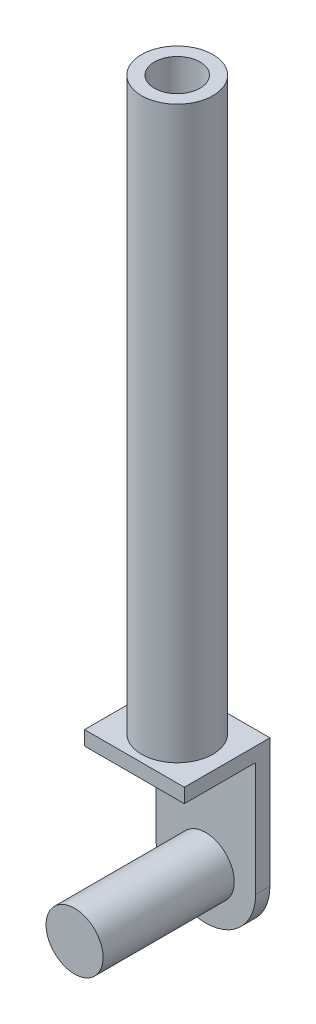
SolidWorks part; units mm, degrees
ref_plane "前视基准面" through (0, 0, 0) normal (0, 0, 1) x (1, 0, 0)
ref_plane "上视基准面" through (0, 0, 0) normal (0, 1, 0) x (1, 0, 0)
ref_plane "右视基准面" through (0, 0, 0) normal (1, 0, 0) x (0, 0, -1)
sketch "草图1" plane through (0, 0, 0) normal (0, 0, 1) x (1, 0, 0)
  line L0 (-17.5, 0) -> (-17.5, 40)
  line L1 (-17.5, 40) -> (17.5, 40)
  line L2 (17.5, 40) -> (17.5, 0)
  circle A0 centre (0, 0) radius 10 construction
  arc A1 (-17.5, 0) -> (17.5, 0) centre (0, 0) ccw
  dimension "D1" = 20
  dimension "D2" = 35
  dimension "D3" = 40
extrude "凸台-拉伸1" add sketch "草图1" along normal blind 5
sketch "草图2" plane through (0, 0, 5) normal (0, 0, 1) x (1, 0, 0)
  circle A0 centre (0, 0) radius 10
  dimension "D1" = 20
extrude "凸台-拉伸2" add sketch "草图2" along normal blind 46
sketch "草图4" plane through (0, 40, 0) normal (0, 1, 0) x (1, 0, 0)
  line L0 (17.5, -5) -> (17.5, 0) construction
  line L1 (-17.5, 0) -> (17.5, 0)
  line L2 (-17.5, 0) -> (-17.5, -30)
  line L3 (-17.5, -30) -> (17.5, -30)
  line L4 (17.5, 0) -> (17.5, -30)
  dimension "D1" = 30
extrude "凸台-拉伸3" add sketch "草图4" along normal blind 5
sketch "草图5" plane through (0, 45, 0) normal (0, 1, 0) x (1, 0, 0)
  line L0 (17.5, -30) -> (17.5, 0) construction
  circle A0 centre (0, -15) radius 12.5
  circle A1 centre (0, -15) radius 8
  point P6 (17.5, -15)
  dimension "D1" = 16
  dimension "D2" = 25
extrude "凸台-拉伸4" add sketch "草图5" along normal blind 200
